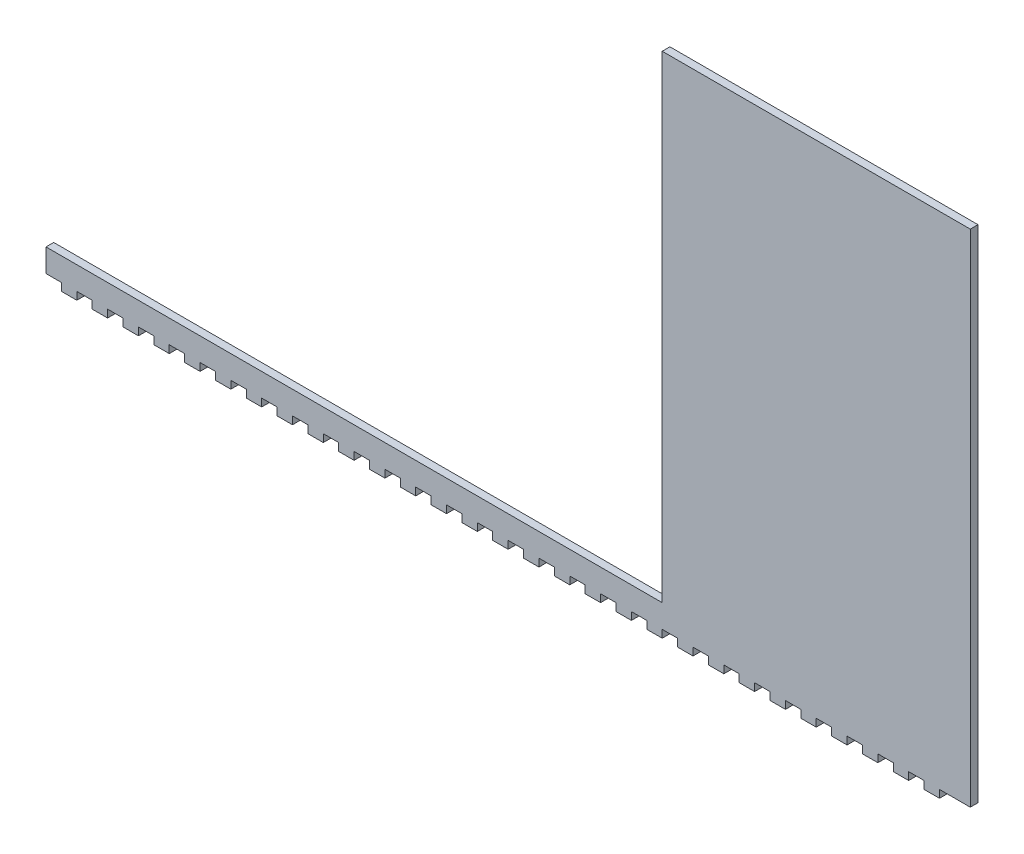
SolidWorks part; units mm, degrees
ref_plane "Plan de face" through (0, 0, 0) normal (0, 0, 1) x (1, 0, 0)
ref_plane "Plan de dessus" through (0, 0, 0) normal (0, 1, 0) x (1, 0, 0)
ref_plane "Plan de droite" through (0, 0, 0) normal (1, 0, 0) x (0, 0, -1)
sketch "Esquisse1" plane through (0, 0, 0) normal (0, 0, 1) x (1, 0, 0)
  line L0 (400, 20) -> (400, 330)
  line L1 (0, 0) -> (400, 0)
  line L2 (0, 0) -> (0, 20)
  line L3 (0, 20) -> (400, 20)
  line L9 (400, 330) -> (600, 330)
  line L10 (600, 330) -> (600, 0)
  line L11 (600, 0) -> (400, 0)
  dimension "D1" = 400
  dimension "D2" = 20
  dimension "D3" = 200
  dimension "D4" = 330
extrude "Boss.-Extru.1" add sketch "Esquisse1" along normal blind 5
sketch "Esquisse2" plane through (0, 0, 5) normal (0, 0, 1) x (1, 0, 0)
  line L0 (20, 0) -> (20, 5)
  line L1 (0, 0) -> (10, 0)
  line L2 (0, 0) -> (0, 5)
  line L3 (0, 5) -> (10, 5)
  line L4 (10, 0) -> (10, 5)
  line L5 (20, 0) -> (30, 0)
  line L6 (30, 0) -> (30, 5)
  line L7 (20, 5) -> (30, 5)
  line L8 (40, 0) -> (40, 5)
  line L9 (40, 0) -> (50, 0)
  line L10 (50, 0) -> (50, 5)
  line L11 (40, 5) -> (50, 5)
  line L12 (60, 0) -> (60, 5)
  line L13 (60, 0) -> (70, 0)
  line L14 (70, 0) -> (70, 5)
  line L15 (60, 5) -> (70, 5)
  line L16 (80, 0) -> (80, 5)
  line L17 (80, 0) -> (90, 0)
  line L18 (90, 0) -> (90, 5)
  line L19 (80, 5) -> (90, 5)
  line L20 (100, 0) -> (100, 5)
  line L21 (100, 0) -> (110, 0)
  line L22 (110, 0) -> (110, 5)
  line L23 (100, 5) -> (110, 5)
  line L24 (120, 0) -> (120, 5)
  line L25 (120, 0) -> (130, 0)
  line L26 (130, 0) -> (130, 5)
  line L27 (120, 5) -> (130, 5)
  line L28 (140, 0) -> (140, 5)
  line L29 (140, 0) -> (150, 0)
  line L30 (150, 0) -> (150, 5)
  line L31 (140, 5) -> (150, 5)
  line L32 (160, 0) -> (160, 5)
  line L33 (160, 0) -> (170, 0)
  line L34 (170, 0) -> (170, 5)
  line L35 (160, 5) -> (170, 5)
  line L36 (180, 0) -> (180, 5)
  line L37 (180, 0) -> (190, 0)
  line L38 (190, 0) -> (190, 5)
  line L39 (180, 5) -> (190, 5)
  line L40 (200, 0) -> (200, 5)
  line L41 (200, 0) -> (210, 0)
  line L42 (210, 0) -> (210, 5)
  line L43 (200, 5) -> (210, 5)
  line L44 (220, 0) -> (220, 5)
  line L45 (220, 0) -> (230, 0)
  line L46 (230, 0) -> (230, 5)
  line L47 (220, 5) -> (230, 5)
  line L48 (240, 0) -> (240, 5)
  line L49 (240, 0) -> (250, 0)
  line L50 (250, 0) -> (250, 5)
  line L51 (240, 5) -> (250, 5)
  line L52 (260, 0) -> (260, 5)
  line L53 (260, 0) -> (270, 0)
  line L54 (270, 0) -> (270, 5)
  line L55 (260, 5) -> (270, 5)
  line L56 (280, 0) -> (280, 5)
  line L57 (280, 0) -> (290, 0)
  line L58 (290, 0) -> (290, 5)
  line L59 (280, 5) -> (290, 5)
  line L60 (300, 0) -> (300, 5)
  line L61 (300, 0) -> (310, 0)
  line L62 (310, 0) -> (310, 5)
  line L63 (300, 5) -> (310, 5)
  line L64 (320, 0) -> (320, 5)
  line L65 (320, 0) -> (330, 0)
  line L66 (330, 0) -> (330, 5)
  line L67 (320, 5) -> (330, 5)
  line L68 (340, 0) -> (340, 5)
  line L69 (340, 0) -> (350, 0)
  line L70 (350, 0) -> (350, 5)
  line L71 (340, 5) -> (350, 5)
  line L72 (360, 0) -> (360, 5)
  line L73 (360, 0) -> (370, 0)
  line L74 (370, 0) -> (370, 5)
  line L75 (360, 5) -> (370, 5)
  line L76 (380, 0) -> (380, 5)
  line L77 (380, 0) -> (390, 0)
  line L78 (390, 0) -> (390, 5)
  line L79 (380, 5) -> (390, 5)
  line L80 (400, 0) -> (400, 5)
  line L81 (400, 0) -> (410, 0)
  line L82 (410, 0) -> (410, 5)
  line L83 (400, 5) -> (410, 5)
  line L84 (420, 0) -> (420, 5)
  line L85 (420, 0) -> (430, 0)
  line L86 (430, 0) -> (430, 5)
  line L87 (420, 5) -> (430, 5)
  line L88 (440, 0) -> (440, 5)
  line L89 (440, 0) -> (450, 0)
  line L90 (450, 0) -> (450, 5)
  line L91 (440, 5) -> (450, 5)
  line L92 (460, 0) -> (460, 5)
  line L93 (460, 0) -> (470, 0)
  line L94 (470, 0) -> (470, 5)
  line L95 (460, 5) -> (470, 5)
  line L100 (480, 0) -> (480, 5)
  line L105 (490, 0) -> (490, 5) [skipped]
  line L165 (480, 0) -> (480, 5) [skipped]
  line L166 (480, 5) -> (490, 5) [skipped]
  line L167 (480, 0) -> (490, 0) [skipped]
  line L168 (480, 5) -> (490, 5)
  line L169 (490, 0) -> (490, 5)
  line L170 (480, 0) -> (490, 0)
  line L171 (500, 0) -> (500, 5)
  line L172 (500, 5) -> (510, 5)
  line L173 (510, 0) -> (510, 5)
  line L174 (500, 0) -> (510, 0)
  line L175 (520, 0) -> (520, 5)
  line L176 (520, 5) -> (530, 5)
  line L177 (530, 0) -> (530, 5)
  line L178 (520, 0) -> (530, 0)
  line L179 (540, 0) -> (540, 5)
  line L180 (540, 5) -> (550, 5)
  line L181 (550, 0) -> (550, 5)
  line L182 (540, 0) -> (550, 0)
  line L183 (560, 0) -> (560, 5)
  line L184 (560, 5) -> (570, 5)
  line L185 (570, 0) -> (570, 5)
  line L186 (560, 0) -> (570, 0)
  line L187 (580, 0) -> (580, 5)
  line L188 (580, 5) -> (590, 5)
  line L190 (580, 0) -> (590, 0)
  line L192 (590, 5) -> (600, 5)
  line L193 (600, 0) -> (600, 5)
  line L194 (590, 0) -> (600, 0)
  line L195 (590, 0) -> (590, 5) [skipped]
  line L196 (590, 0) -> (590, 5) [skipped]
  dimension "D1" = 10
  dimension "D2" = 5
  dimension "D4" = 7
  dimension "D3" = 25
  dimension "D9" = 2
extrude "Enlèv. mat.-Extru.2" cut sketch "Esquisse2" against normal through all
